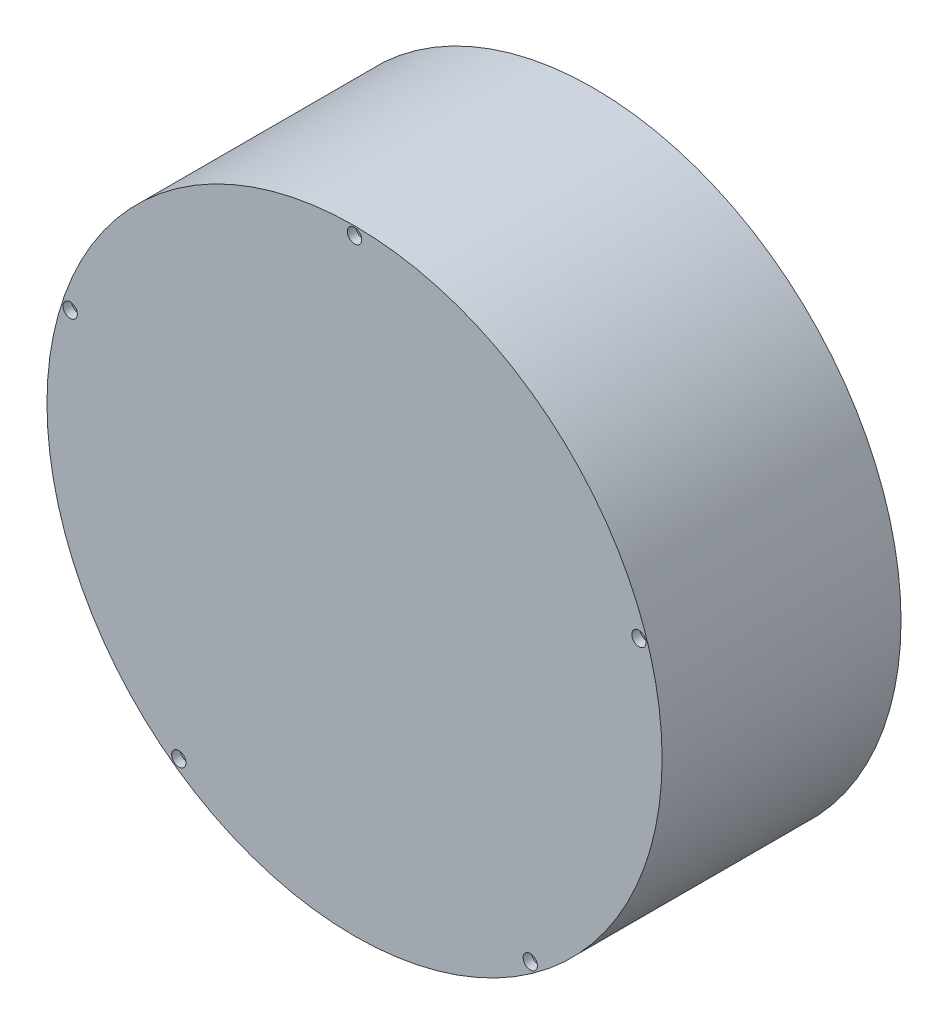
SolidWorks part; units mm, degrees
ref_plane "Front Plane" through (0, 0, 0) normal (0, 0, 1) x (1, 0, 0)
ref_plane "Top Plane" through (0, 0, 0) normal (0, 1, 0) x (1, 0, 0)
ref_plane "Right Plane" through (0, 0, 0) normal (1, 0, 0) x (0, 0, -1)
sketch "Sketch1" plane through (0, 0, 0) normal (0, 0, 1) x (1, 0, 0)
  circle A0 centre (0, 0) radius 215
extrude "Body" add sketch "Sketch1" along normal blind 167
sketch "Sketch2" plane through (0, 0, 0) normal (0, 0, 1) x (1, 0, 0)
  circle A0 centre (0, 0) radius 212
extrude "Cavity" cut sketch "Sketch2" along normal blind 157
ref_plane "Plane_z157" through (0, 0, 157) normal (0, 0, 1) x (1, 0, 0)
sketch "Sketch3" plane through (0, 0, 157) normal (0, 0, 1) x (1, 0, 0)
  circle A0 centre (198.7708, 64.5846) radius 2.75
  circle A1 centre (0, 209) radius 2.75
  circle A2 centre (-198.7708, 64.5846) radius 2.75
  circle A3 centre (-122.8471, -169.0846) radius 2.75
  circle A4 centre (122.8471, -169.0846) radius 2.75
extrude "Rod_holes" cut sketch "Sketch3" along normal blind 10
ref_plane "Plane_z161" through (0, 0, 161) normal (0, 0, 1) x (1, 0, 0)
sketch "Sketch4" plane through (0, 0, 161) normal (0, 0, 1) x (1, 0, 0)
  circle A0 centre (198.7708, 64.5846) radius 5
  circle A1 centre (0, 209) radius 5
  circle A2 centre (-198.7708, 64.5846) radius 5
  circle A3 centre (-122.8471, -169.0846) radius 5
  circle A4 centre (122.8471, -169.0846) radius 5
extrude "Nut_counterbores" cut sketch "Sketch4" along normal blind 6
